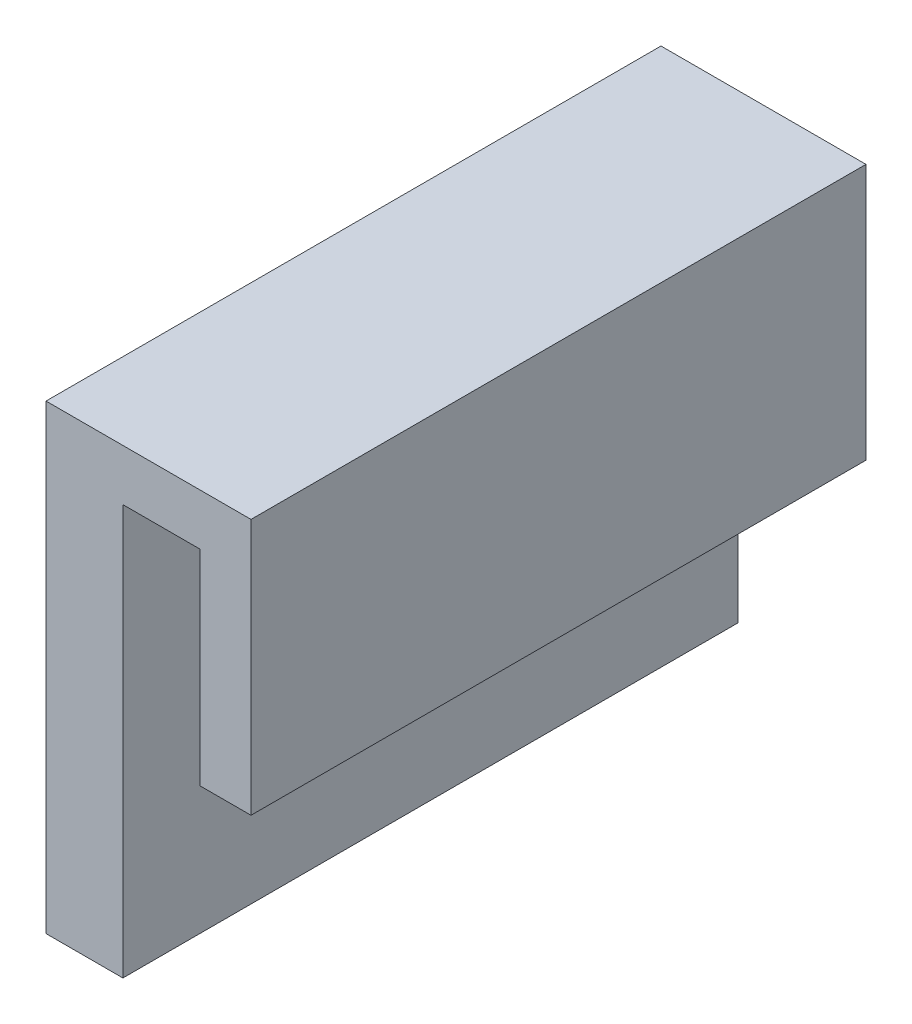
SolidWorks part; units mm, degrees
ref_plane "前视基准面" through (0, 0, 0) normal (0, 0, 1) x (1, 0, 0)
ref_plane "上视基准面" through (0, 0, 0) normal (0, 1, 0) x (1, 0, 0)
ref_plane "右视基准面" through (0, 0, 0) normal (1, 0, 0) x (0, 0, -1)
sketch "草图1" plane through (0, 0, 0) normal (0, 0, 1) x (1, 0, 0)
  line L0 (0, 0) -> (0, -8)
  line L1 (0, -8) -> (1.5, -8)
  line L2 (1.5, -8) -> (1.5, 0)
  line L3 (1.5, 0) -> (3, 0)
  line L4 (3, 0) -> (3, -4)
  line L5 (3, -4) -> (4, -4)
  line L6 (4, -4) -> (4, 1)
  line L7 (4, 1) -> (0, 1)
  line L8 (0, 1) -> (0, 0)
  dimension "D1" = 4
  dimension "D2" = 9
  dimension "D3" = 1
  dimension "D4" = 5
  dimension "D5" = 1
  dimension "D6" = 1.5
extrude "凸台-拉伸1" add sketch "草图1" along normal blind 12
